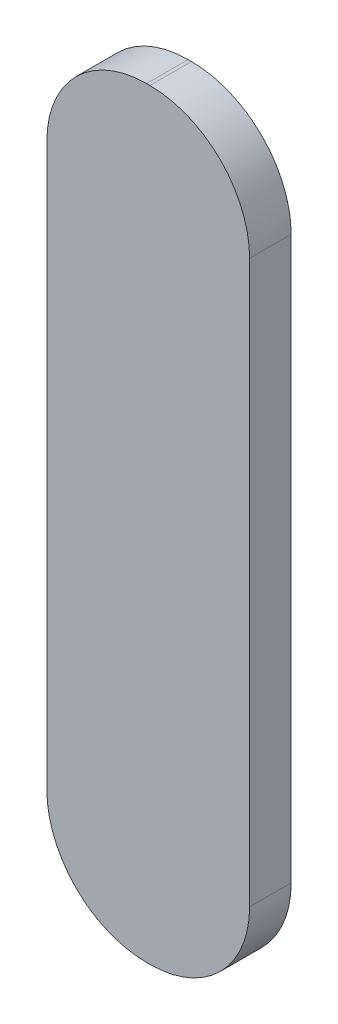
SolidWorks part; units mm, degrees
ref_plane "Front Plane" through (0, 0, 0) normal (0, 0, 1) x (1, 0, 0)
ref_plane "Top Plane" through (0, 0, 0) normal (0, 1, 0) x (1, 0, 0)
ref_plane "Right Plane" through (0, 0, 0) normal (1, 0, 0) x (0, 0, -1)
other "Graphic1"
other "object_1 (Open) -1"
ref_plane "Plane1" through (0, 0, 10) normal (0, 0, 1) x (1, 0, 0)
sketch "Sketch1" plane through (0, 0, 10) normal (0, 0, 1) x (1, 0, 0)
  line L1 (-188.2312, 182.8882) -> (-176.0312, 182.8882)
  line L2 (-188.2312, 182.8882) -> (-188.2312, 137.0882)
  line L3 (-188.2312, 137.0882) -> (-176.0312, 137.0882)
  line L4 (-176.0312, 182.8882) -> (-176.0312, 137.0882)
  point P4 (-188.2312, 182.8882)
  dimension "D1" = 12.2
  dimension "D2" = 45.8
extrude "Boss-Extrude1" add sketch "Sketch1" along normal blind 2.5
fillet "Fillet1" radius 6 4 edges at (-176.0312, 182.8882, 11.25) (-188.2312, 182.8882, 11.25) (-176.0312, 137.0882, 11.25) (-188.2312, 137.0882, 11.25)
sketch "Sketch2" plane through (0, 0, 12.5) normal (0, 0, 1) x (1, 0, 0)
  line L0 (-188.2312, 159.9882) -> (-158.6206, 159.9882) construction
  line L1 (-188.2312, 176.8882) -> (-188.2312, 143.0882) construction
  line L2 (-176.0312, 143.0882) -> (-176.0312, 176.8882) construction
  line L3 (-176.0312, 162.9655) -> (-188.2312, 162.9655)
  line L4 (-176.0312, 162.9655) -> (-176.0312, 182.9655)
  line L5 (-176.0312, 182.9655) -> (-188.2312, 182.9655)
  line L6 (-188.2312, 162.9655) -> (-188.2312, 182.9655)
  dimension "D1" = 20
  dimension "D2" = 12.2
